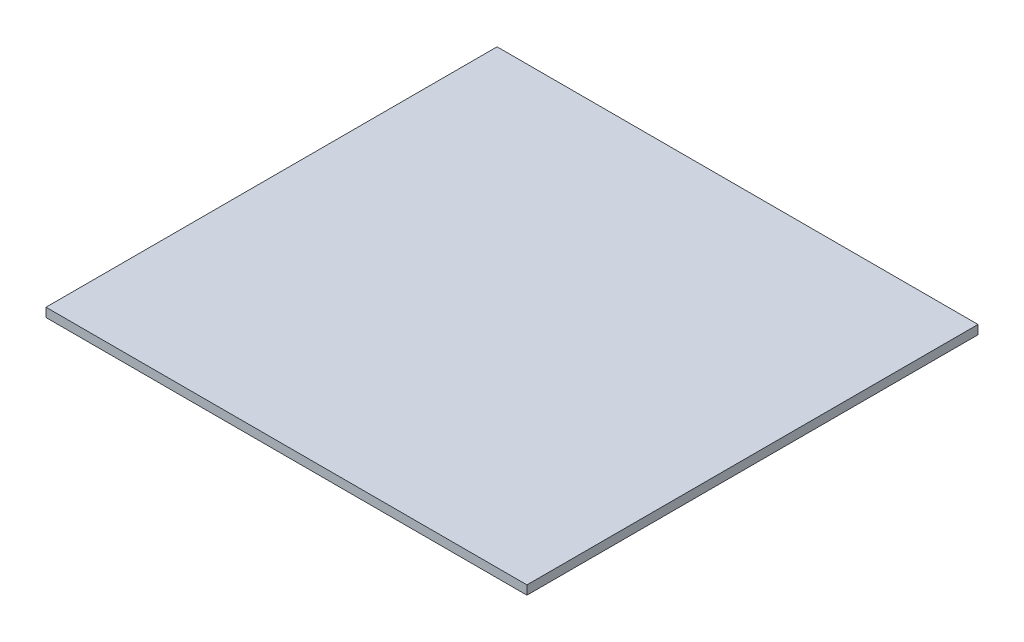
SolidWorks part; units mm, degrees
ref_plane "Front Plane" through (0, 0, 0) normal (0, 0, 1) x (1, 0, 0)
ref_plane "Top Plane" through (0, 0, 0) normal (0, 1, 0) x (1, 0, 0)
ref_plane "Right Plane" through (0, 0, 0) normal (1, 0, 0) x (0, 0, -1)
sketch "Sketch1" plane through (0, 0, 0) normal (0, 1, 0) x (1, 0, 0)
  line L1 (-116.236, 164.2077) -> (44.764, 164.2077)
  line L2 (-116.236, 164.2077) -> (-116.236, 13.2077)
  line L3 (-116.236, 13.2077) -> (44.764, 13.2077)
  line L4 (44.764, 164.2077) -> (44.764, 13.2077)
  line L5 (-116.236, 164.2077) -> (44.764, 13.2077) construction
  line L6 (-116.236, 13.2077) -> (44.764, 164.2077) construction
  point P0 (-35.736, 88.7077)
  dimension "D1" = 161
  dimension "D2" = 151
extrude "Boss-Extrude1" add sketch "Sketch1" along normal blind 3
